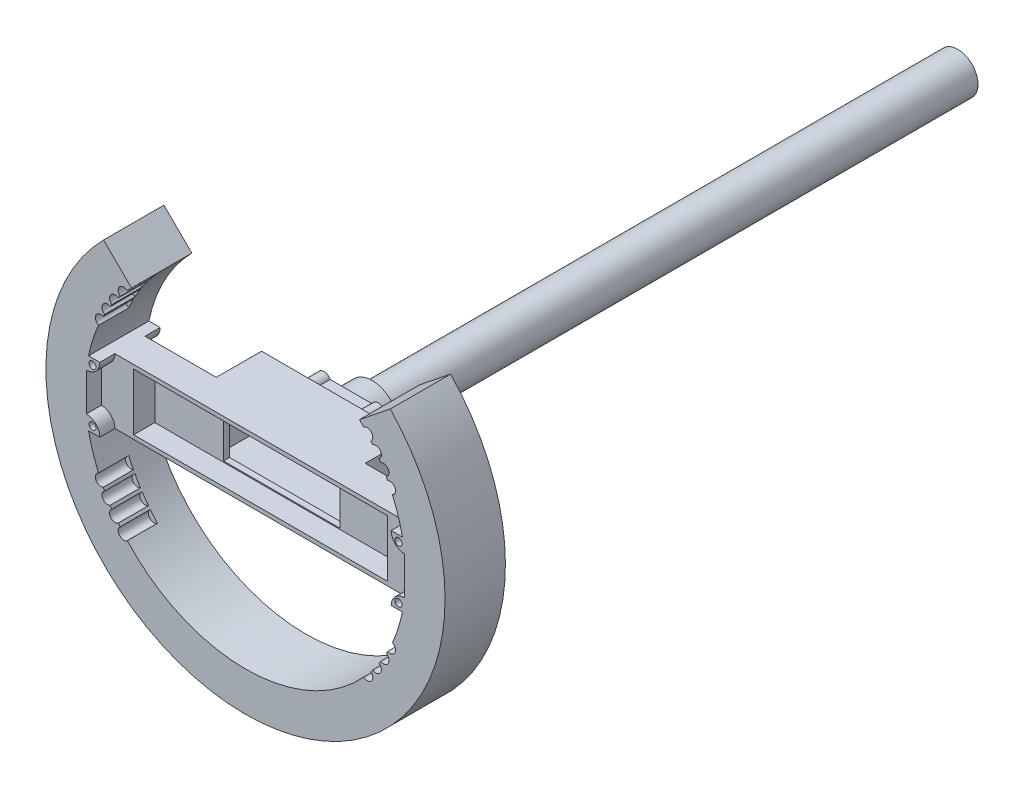
SolidWorks part; units mm, degrees
ref_plane "Front Plane" through (0, 0, 0) normal (0, 0, 1) x (1, 0, 0)
ref_plane "Top Plane" through (0, 0, 0) normal (0, 1, 0) x (1, 0, 0)
ref_plane "Right Plane" through (0, 0, 0) normal (1, 0, 0) x (0, 0, -1)
sketch "Sketch1" plane through (0, 0, 0) normal (0, 0, 1) x (1, 0, 0)
  line L0 (52.7324, 21.4981) -> (52.7324, 0) construction
  line L1 (0, 0) -> (105.4649, 0)
  line L2 (0, 0) -> (0, 21.4981)
  line L3 (0, 21.4981) -> (105.4649, 21.4981)
  line L4 (105.4649, 0) -> (105.4649, 21.4981)
  line L5 (0, 10.7491) -> (105.4649, 10.7491)
  arc A0 (0, 17.0337) -> (4.4644, 21.4981) centre (0, 21.4981) ccw
  arc A1 (0, 4.4644) -> (4.4644, 0) centre (0, 0) cw
  arc A2 (105.4649, 4.4644) -> (101.0005, 0) centre (105.4649, 0) ccw
  arc A3 (105.4649, 17.0337) -> (101.0005, 21.4981) centre (105.4649, 21.4981) cw
extrude "Boss-Extrude1" add sketch "Sketch1" along normal blind 10 contours L0 L3 A0 L2 L5 | L0 L5 L2 A1 L1 | L3 L0 L5 L4 A3 | L5 L0 L1 A2 L4
sketch "Sketch2" plane through (0, 0, 0) normal (0, 0, 1) x (1, 0, 0)
  line L0 (52.7324, 21.4981) -> (52.7324, 0)
  line L1 (4.4644, 21.4981) -> (101.0005, 21.4981) construction
  line L2 (4.4644, 0) -> (101.0005, 0) construction
  line L3 (0, 10.7491) -> (105.4649, 10.7491)
  line L4 (0, 4.4644) -> (0, 17.0337) construction
  line L5 (105.4649, 4.4644) -> (105.4649, 17.0337) construction
  line L6 (14.9658, 48.0839) -> (5.7089, 57.2349)
  line L7 (90.4991, 48.0839) -> (100.7154, 56.244)
  line L8 (0, 17.0337) -> (0, 4.4644)
  line L9 (105.4649, 17.0337) -> (105.4649, 4.4644)
  arc A0 (0, 17.0337) -> (14.9658, 48.0839) centre (52.7324, 10.7491) cw
  arc A1 (0, 4.4644) -> (105.4649, 4.4644) centre (52.7324, 10.7491) ccw
  arc A2 (105.4649, 4.4644) -> (101.0005, 0) centre (105.4649, 0) ccw construction
  arc A3 (105.4649, 17.0337) -> (90.4991, 48.0839) centre (52.7324, 10.7491) ccw
  circle A4 centre (52.7324, 10.7491) radius 66.1223
extrude "Boss-Extrude2" add sketch "Sketch2" along normal blind 15 and the other way blind 5 contours L6 A4 L7 A3 L9 A1 L8 A0
sketch "Sketch5" plane through (0, 0, 15) normal (0, 0, 1) x (1, 0, 0)
  line L0 (52.7324, 10.7491) -> (52.7324, 22.8173)
  line L1 (52.7324, 10.7491) -> (77.358, 10.7491)
  line L4 (14.9658, 48.0839) -> (5.7089, 57.2349)
  line L5 (100.7154, 56.244) -> (90.4991, 48.0839)
  line L6 (105.4649, 17.0337) -> (105.4649, 4.4644)
  line L7 (0, 4.4644) -> (0, 17.0337)
  line L8 (14.9658, 48.0839) -> (5.7089, 57.2349)
  line L9 (100.7154, 56.244) -> (90.4991, 48.0839)
  line L10 (105.4649, 17.0337) -> (105.4649, 4.4644)
  line L11 (0, 4.4644) -> (0, 17.0337)
  arc A0 (13.5675, 46.6143) -> (11.1916, 43.8333) centre (12.3796, 45.2238) ccw
  arc A1 (10.5907, 43.0644) -> (8.4662, 40.0869) centre (9.5284, 41.5756) ccw
  arc A2 (7.9346, 39.2685) -> (6.0777, 36.1172) centre (7.0061, 37.6928) ccw
  arc A3 (5.6194, 35.2556) -> (4.0443, 31.9544) centre (4.8318, 33.605) ccw
  arc A4 (5.7089, 57.2349) -> (100.7154, 56.244) centre (52.7324, 10.7491) ccw
  arc A5 (105.4649, 17.0337) -> (90.4991, 48.0839) centre (52.7324, 10.7491) ccw
  arc A6 (0, 4.4644) -> (105.4649, 4.4644) centre (52.7324, 10.7491) ccw
  arc A7 (14.9658, 48.0839) -> (0, 17.0337) centre (52.7324, 10.7491) ccw
  arc A8 (5.7089, 57.2349) -> (100.7154, 56.244) centre (52.7324, 10.7491) ccw
  arc A9 (105.4649, 17.0337) -> (90.4991, 48.0839) centre (52.7324, 10.7491) ccw
  arc A10 (0, 4.4644) -> (105.4649, 4.4644) centre (52.7324, 10.7491) ccw
  arc A11 (14.9658, 48.0839) -> (0, 17.0337) centre (52.7324, 10.7491) ccw
  arc A12 (99.8455, 35.2556) -> (101.4206, 31.9544) centre (100.633, 33.605) cw
  arc A13 (97.5303, 39.2685) -> (99.3872, 36.1172) centre (98.4587, 37.6928) cw
  arc A14 (94.8742, 43.0644) -> (96.9986, 40.0869) centre (95.9364, 41.5756) cw
  arc A15 (91.8974, 46.6143) -> (94.2732, 43.8333) centre (93.0853, 45.2238) cw
  arc A16 (91.8974, -25.1162) -> (94.2732, -22.3352) centre (93.0853, -23.7257) ccw
  arc A17 (94.8742, -21.5663) -> (96.9986, -18.5888) centre (95.9364, -20.0775) ccw
  arc A18 (97.5303, -17.7704) -> (99.3872, -14.6191) centre (98.4587, -16.1947) ccw
  arc A19 (99.8455, -13.7575) -> (101.4206, -10.4563) centre (100.633, -12.1069) ccw
  arc A20 (5.6194, -13.7575) -> (4.0443, -10.4563) centre (4.8318, -12.1069) cw
  arc A21 (7.9346, -17.7704) -> (6.0777, -14.6191) centre (7.0061, -16.1947) cw
  arc A22 (10.5907, -21.5663) -> (8.4662, -18.5888) centre (9.5284, -20.0775) cw
  arc A23 (13.5675, -25.1162) -> (11.1916, -22.3352) centre (12.3796, -23.7257) cw
  point P27 (52.7324, 10.7491)
  point P63 (0, 0)
  arc M21 (0, 17.0337) -> (14.9658, 48.0839) centre (52.7324, 10.7491) cw
  dimension "D1" = 0
  dimension "D2" = 4
extrude "Cut-Extrude1" cut sketch "Sketch5" against normal blind 10 contours A3 M21 | A2 M21 | A1 M21 | A0 M21 | A12 A9 | A13 A9 | A14 A9 | A15 A9 | A20 A10 | A21 A10 | A22 A10 | A23 A10 | A10 A16 | A10 A17 | A10 A18 | A10 A19
sketch "Sketch6" plane through (0, 0, 10) normal (0, 0, 1) x (1, 0, 0)
  line L0 (52.7324, 21.4981) -> (52.7324, 0)
  line L2 (10.6722, 1.3264) -> (94.7927, 1.3264)
  line L3 (10.6722, 1.3264) -> (10.6722, 20.1717)
  line L4 (105.4649, 4.4644) -> (105.4649, 17.0337)
  line L5 (101.0005, 21.4981) -> (4.4644, 21.4981)
  line L6 (0, 17.0337) -> (0, 4.4644)
  line L7 (4.4644, 0) -> (101.0005, 0)
  line L8 (105.4649, 4.4644) -> (105.4649, 17.0337)
  line L9 (101.0005, 21.4981) -> (4.4644, 21.4981)
  line L10 (0, 17.0337) -> (0, 4.4644)
  line L11 (4.4644, 0) -> (101.0005, 0)
  line L12 (10.6722, 20.1717) -> (94.7927, 20.1717)
  line L13 (94.7927, 1.3264) -> (94.7927, 20.1717)
  line L14 (10.6722, 1.3264) -> (94.7927, 20.1717) construction
  line L15 (10.6722, 20.1717) -> (94.7927, 1.3264) construction
  arc A4 (105.4649, 4.4644) -> (101.0005, 0) centre (105.4649, 0) ccw
  arc A5 (101.0005, 21.4981) -> (105.4649, 17.0337) centre (105.4649, 21.4981) ccw
  arc A6 (0, 17.0337) -> (4.4644, 21.4981) centre (0, 21.4981) ccw
  arc A7 (4.4644, 0) -> (0, 4.4644) centre (0, 0) ccw
  arc A8 (105.4649, 4.4644) -> (101.0005, 0) centre (105.4649, 0) ccw
  arc A9 (101.0005, 21.4981) -> (105.4649, 17.0337) centre (105.4649, 21.4981) ccw
  arc A10 (0, 17.0337) -> (4.4644, 21.4981) centre (0, 21.4981) ccw
  arc A11 (4.4644, 0) -> (0, 4.4644) centre (0, 0) ccw
  point P10 (52.7324, 10.7491)
  dimension "D1" = 0
extrude "Cut-Extrude2" cut sketch "Sketch6" against normal offset from surface (7 mm away) 3 contours L2 L13 L12 L0 | L12 L3 L2 L0 up to face at (52.7324, 10.7491, 0)
sketch "Sketch7" plane through (0, 0, 0) normal (0, 0, -1) x (-1, 0, 0)
  line L0 (-52.7324, 21.4981) -> (-52.7324, 0)
  line L1 (-4.4644, 21.4981) -> (-101.0005, 21.4981) construction
  line L2 (-4.4644, 0) -> (-101.0005, 0) construction
  line L4 (-72.0328, 1.7078) -> (-33.432, 1.7078)
  line L5 (-72.0328, 1.7078) -> (-72.0328, 19.7903)
  line L6 (-72.0328, 19.7903) -> (-33.432, 19.7903)
  line L7 (-33.432, 1.7078) -> (-33.432, 19.7903)
  line L8 (-72.0328, 1.7078) -> (-33.432, 19.7903) construction
  line L9 (-72.0328, 19.7903) -> (-33.432, 1.7078) construction
  point P6 (-52.7324, 10.7491)
extrude "Cut-Extrude3" cut sketch "Sketch7" against normal up to surface (3 mm away) contours L6 L5 L4 L0 | L4 L7 L6 L0 up to face at (52.7324, 10.7491, 3)
sketch "Sketch8" plane through (0, 0, 0) normal (0, 0, -1) x (-1, 0, 0)
  line L0 (-52.7324, 21.4981) -> (-52.7324, 0)
  line L2 (-74.5468, 0.6395) -> (-30.918, 0.6395)
  line L3 (-74.5468, 0.6395) -> (-74.5468, 20.8586)
  line L4 (-101.0005, 0) -> (-4.4644, 0)
  line L5 (0, 4.4644) -> (0, 17.0337)
  line L6 (-4.4644, 21.4981) -> (-101.0005, 21.4981)
  line L7 (-105.4649, 17.0337) -> (-105.4649, 4.4644)
  line L8 (-101.0005, 0) -> (-4.4644, 0)
  line L9 (0, 4.4644) -> (0, 17.0337)
  line L10 (-4.4644, 21.4981) -> (-101.0005, 21.4981)
  line L11 (-105.4649, 17.0337) -> (-105.4649, 4.4644)
  line L12 (-74.5468, 20.8586) -> (-30.918, 20.8586)
  line L13 (-30.918, 0.6395) -> (-30.918, 20.8586)
  line L14 (-74.5468, 0.6395) -> (-30.918, 20.8586) construction
  line L15 (-74.5468, 20.8586) -> (-30.918, 0.6395) construction
  arc A4 (-101.0005, 0) -> (-105.4649, 4.4644) centre (-105.4649, 0) ccw
  arc A5 (0, 4.4644) -> (-4.4644, 0) centre (0, 0) ccw
  arc A6 (-4.4644, 21.4981) -> (0, 17.0337) centre (0, 21.4981) ccw
  arc A7 (-105.4649, 17.0337) -> (-101.0005, 21.4981) centre (-105.4649, 21.4981) ccw
  arc A8 (-101.0005, 0) -> (-105.4649, 4.4644) centre (-105.4649, 0) ccw
  arc A9 (0, 4.4644) -> (-4.4644, 0) centre (0, 0) ccw
  arc A10 (-4.4644, 21.4981) -> (0, 17.0337) centre (0, 21.4981) ccw
  arc A11 (-105.4649, 17.0337) -> (-101.0005, 21.4981) centre (-105.4649, 21.4981) ccw
  point P10 (-52.7324, 10.7491)
  line M17 (-72.0328, 19.7903) -> (-33.432, 19.7903)
  line M18 (-33.432, 19.7903) -> (-33.432, 1.7078)
  line M19 (-33.432, 1.7078) -> (-72.0328, 1.7078)
  line M20 (-72.0328, 1.7078) -> (-72.0328, 19.7903)
  dimension "D1" = 0
extrude "Cut-Extrude4" cut sketch "Sketch8" against normal blind 1 contours L12 L3 L2 L0 M19 M20 M17 | L2 L13 L12 L0 M17 M18 M19
sketch "Sketch9" plane through (0, 0, 0) normal (0, 0, -1) x (-1, 0, 0)
  line L0 (-52.7433, 21.4981) -> (-52.7324, 0)
  line L1 (-74.5468, 0.6395) -> (-75.9265, 0.6395)
  line L2 (-77.4105, 0) -> (-28.0652, 0)
  line L3 (-77.4105, 0) -> (-77.4105, 21.4981)
  line L4 (-101.0005, 0) -> (-4.4644, 0)
  line L5 (0, 4.4644) -> (0, 17.0337)
  line L6 (-4.4644, 21.4981) -> (-101.0005, 21.4981)
  line L7 (-105.4649, 17.0337) -> (-105.4649, 4.4644)
  line L8 (-101.0005, 0) -> (-4.4644, 0)
  line L9 (0, 4.4644) -> (0, 17.0337)
  line L10 (-4.4644, 21.4981) -> (-101.0005, 21.4981)
  line L11 (-105.4649, 17.0337) -> (-105.4649, 4.4644)
  line L12 (-77.4105, 21.4981) -> (-28.0652, 21.4981)
  line L13 (-28.0652, 0) -> (-28.0652, 21.4981)
  line L14 (-30.918, 0.6395) -> (-29.5493, 0.6395)
  line L15 (-30.918, 20.8586) -> (-29.5493, 20.8586)
  line L16 (-75.9265, 0) -> (-29.5493, 0)
  line L17 (-75.9265, 0) -> (-75.9265, 21.4981)
  line L18 (-75.9265, 21.4981) -> (-29.5493, 21.4981)
  line L19 (-29.5493, 0) -> (-29.5493, 21.4981)
  line L20 (-74.5468, 20.8586) -> (-75.9265, 20.8586)
  arc A4 (-101.0005, 0) -> (-105.4649, 4.4644) centre (-105.4649, 0) ccw
  arc A5 (0, 4.4644) -> (-4.4644, 0) centre (0, 0) ccw
  arc A6 (-4.4644, 21.4981) -> (0, 17.0337) centre (0, 21.4981) ccw
  arc A7 (-105.4649, 17.0337) -> (-101.0005, 21.4981) centre (-105.4649, 21.4981) ccw
  arc A8 (-101.0005, 0) -> (-105.4649, 4.4644) centre (-105.4649, 0) ccw
  arc A9 (0, 4.4644) -> (-4.4644, 0) centre (0, 0) ccw
  arc A10 (-4.4644, 21.4981) -> (0, 17.0337) centre (0, 21.4981) ccw
  arc A11 (-105.4649, 17.0337) -> (-101.0005, 21.4981) centre (-105.4649, 21.4981) ccw
  point P10 (-52.7379, 10.7491)
  point P19 (-52.7379, 10.7491)
  line M10 (-30.918, 0.6395) -> (-74.5468, 0.6395)
  line M12 (-74.5468, 20.8586) -> (-30.918, 20.8586)
  line M14 (-101.0005, 0) -> (-4.4644, 0)
  line M18 (-4.4644, 21.4981) -> (-101.0005, 21.4981)
  dimension "D1" = 0
extrude "Boss-Extrude3" add sketch "Sketch9" along normal blind 15 contours L20 L0 L17 M12 M18 | L15 L19 L12 L0 M12 | L17 L12 L3 M14 | L17 L8 L0 L1 M10 | L19 L14 L0 M14 M10 | L19 L8 L13 L10
sketch "Sketch10" plane through (0, 0, -15) normal (0, 0, -1) x (-1, 0, 0)
  line L1 (-75.9265, 20.8586) -> (-29.5493, 20.8586)
  line L2 (-75.9265, 20.8586) -> (-75.9265, 0.6395)
  line L3 (-75.9265, 0.6395) -> (-29.5493, 0.6395)
  line L4 (-29.5493, 20.8586) -> (-29.5493, 0.6395)
extrude "Boss-Extrude4" add sketch "Sketch10" against normal blind 3
sketch "Sketch11" plane through (0, 0, -15) normal (0, 0, -1) x (-1, 0, 0)
  line L0 (-52.7379, 21.4981) -> (-52.7379, 0)
  line L4 (-77.4105, 0) -> (-28.0652, 0)
  line L5 (-28.0652, 0) -> (-28.0652, 21.4981)
  line L6 (-28.0652, 21.4981) -> (-77.4105, 21.4981)
  line L7 (-77.4105, 21.4981) -> (-77.4105, 0)
  line L8 (-77.4105, 0) -> (-28.0652, 0)
  line L9 (-28.0652, 0) -> (-28.0652, 21.4981)
  line L10 (-28.0652, 21.4981) -> (-77.4105, 21.4981)
  line L11 (-77.4105, 21.4981) -> (-77.4105, 0)
  circle A0 centre (-52.7379, 10.7491) radius 6.6678
  circle A1 centre (-52.7379, 10.7491) radius 8.6678
  dimension "D1" = 0
  dimension "D2" = 2
extrude "Boss-Extrude5" add sketch "Sketch11" along normal blind 12 contours L0 A1 A0 | L0 A1 A0
sketch "Sketch12" plane through (0, 0, -15) normal (0, 0, -1) x (-1, 0, 0)
  line L0 (-52.7379, 19.7491) -> (-52.7379, 1.7491)
  line L1 (-62.7379, 1.7491) -> (-42.7379, 1.7491)
  line L2 (-62.7379, 1.7491) -> (-62.7379, 19.7491)
  line L3 (-62.7379, 19.7491) -> (-45.763, 19.7491)
  line L4 (-42.7379, 1.7491) -> (-42.7379, 16.8786)
  line L5 (-62.7379, 1.7491) -> (-42.7379, 19.7491) construction
  line L6 (-62.7379, 19.7491) -> (-42.7379, 1.7491) construction
  line L7 (-62.7379, 10.7491) -> (-42.7379, 10.7491)
  arc A0 (-62.7379, 4.6195) -> (-59.7128, 1.7491) centre (-61.7059, 2.6778) ccw
  arc A1 (-42.7379, 4.6195) -> (-45.763, 1.7491) centre (-43.7698, 2.6778) cw
  arc A2 (-62.7379, 16.8786) -> (-59.7128, 19.7491) centre (-61.7059, 18.8203) cw
  arc A3 (-42.7379, 16.8786) -> (-45.763, 19.7491) centre (-43.7698, 18.8203) ccw
  circle A4 centre (-61.7059, 18.8203) radius 0.859
  circle A5 centre (-61.7059, 2.6778) radius 0.859
  circle A6 centre (-43.7698, 18.8203) radius 0.859
  circle A7 centre (-43.7698, 2.6778) radius 0.859
  point P0 (-52.7379, 10.7491)
  circle M6 centre (-52.7379, 10.7491) radius 8.6678
  dimension "D1" = 18
  dimension "D2" = 20
extrude "Boss-Extrude6" add sketch "Sketch12" along normal blind 5 contours A2 L2 L3 | L2 L7 L0 L3 A4 M6 | L4 A3 L3 L0 L7 A6 M6 | L7 L0 L1 L4 A7 M6 | A1 L4 L1 | L7 L2 L1 L0 A5 M6 | L2 A0 L1
sketch "Sketch13" plane through (0, 0, 10) normal (0, 0, 1) x (1, 0, 0)
  line L0 (52.7324, 21.4981) -> (52.7324, 0)
  line L1 (101.0005, 0) -> (104.7388, 0)
  line L2 (101.0005, 21.4981) -> (104.7388, 21.4981)
  line L3 (4.4644, 21.4981) -> (0.726, 21.4981)
  line L4 (105.4649, 4.4644) -> (105.4649, 17.0337)
  line L5 (101.0005, 21.4981) -> (4.4644, 21.4981)
  line L6 (0, 17.0337) -> (0, 4.4644)
  line L7 (4.4644, 0) -> (101.0005, 0)
  line L8 (105.4649, 4.4644) -> (105.4649, 17.0337)
  line L9 (101.0005, 21.4981) -> (4.4644, 21.4981)
  line L10 (0, 17.0337) -> (0, 4.4644)
  line L11 (4.4644, 0) -> (101.0005, 0)
  line L12 (4.4644, 0) -> (0.726, 0)
  line L13 (52.7324, 10.7491) -> (80.8283, 10.7491)
  arc A0 (4.0443, 31.9544) -> (0, 17.0337) centre (52.7324, 10.7491) ccw construction
  arc A1 (4.0443, 31.9544) -> (0, 17.0337) centre (52.7324, 10.7491) ccw
  arc A2 (105.4649, 17.0337) -> (101.4206, 31.9544) centre (52.7324, 10.7491) ccw construction
  arc A3 (105.4649, 17.0337) -> (101.4206, 31.9544) centre (52.7324, 10.7491) ccw
  arc A4 (105.4649, 4.4644) -> (101.0005, 0) centre (105.4649, 0) ccw
  arc A5 (101.0005, 21.4981) -> (105.4649, 17.0337) centre (105.4649, 21.4981) ccw
  arc A6 (0, 17.0337) -> (4.4644, 21.4981) centre (0, 21.4981) ccw
  arc A7 (4.4644, 0) -> (0, 4.4644) centre (0, 0) ccw
  arc A8 (105.4649, 4.4644) -> (101.0005, 0) centre (105.4649, 0) ccw
  arc A9 (101.0005, 21.4981) -> (105.4649, 17.0337) centre (105.4649, 21.4981) ccw
  arc A10 (0, 17.0337) -> (4.4644, 21.4981) centre (0, 21.4981) ccw
  arc A11 (4.4644, 0) -> (0, 4.4644) centre (0, 0) ccw
  arc A12 (0, 4.4644) -> (4.0443, -10.4563) centre (52.7324, 10.7491) ccw construction
  arc A13 (0, 4.4644) -> (4.0443, -10.4563) centre (52.7324, 10.7491) ccw
  arc A14 (101.4206, -10.4563) -> (105.4649, 4.4644) centre (52.7324, 10.7491) ccw construction
  arc A15 (101.4206, -10.4563) -> (105.4649, 4.4644) centre (52.7324, 10.7491) ccw
  circle A16 centre (2.0473, 19.5023) radius 1.168
  circle A17 centre (103.4175, 19.5023) radius 1.168
  circle A18 centre (2.0473, 1.9958) radius 1.168
  circle A19 centre (103.4175, 1.9958) radius 1.168
  arc M13 (101.0005, 0) -> (105.4649, 4.4644) centre (105.4649, 0) cw
  arc M15 (105.4649, 17.0337) -> (101.0005, 21.4981) centre (105.4649, 21.4981) cw
  arc M17 (4.4644, 21.4981) -> (0, 17.0337) centre (0, 21.4981) cw
  arc M19 (0, 4.4644) -> (4.4644, 0) centre (0, 0) cw
  dimension "D1" = 0
extrude "Boss-Extrude7" add sketch "Sketch13" along normal up to surface and the other way up to surface contours L3 A1 A16 M17 | A13 L12 A18 M19 | A3 L2 A17 M15 | L1 A15 A19 M13
sketch "Sketch14" plane through (0, 0, -15) normal (0, 0, -1) x (-1, 0, 0)
  circle A0 centre (-52.7379, 10.7491) radius 6.7142
extrude "Boss-Extrude8" add sketch "Sketch14" along normal blind 206
